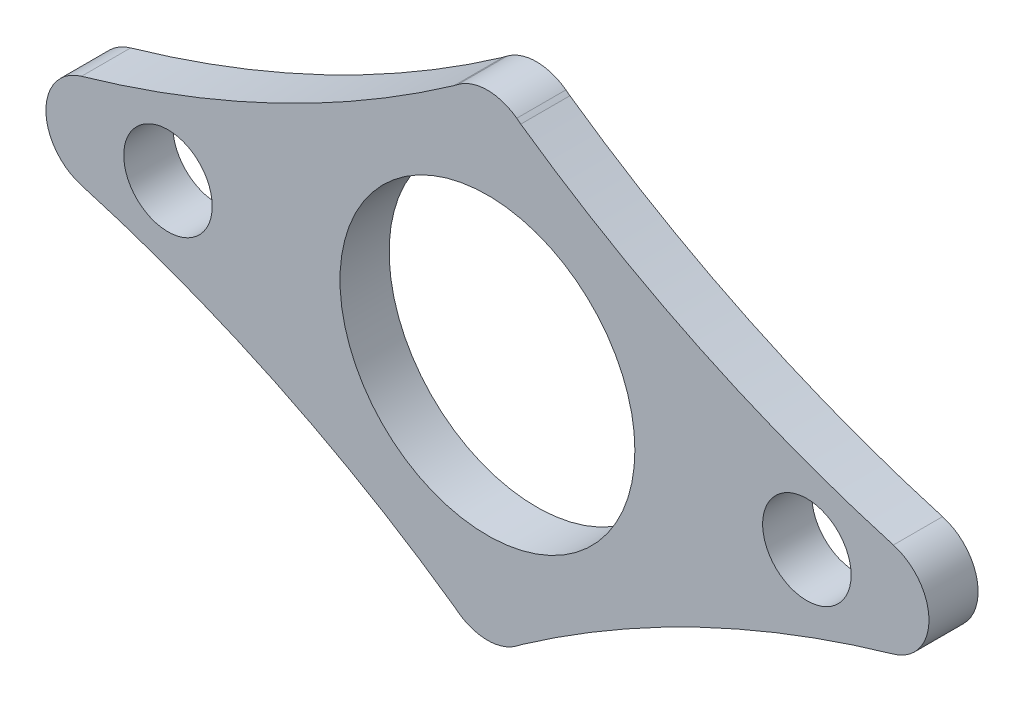
SolidWorks part; units mm, degrees
material "ABS"
ref_plane "Front Plane" through (0, 0, 0) normal (0, 0, 1) x (1, 0, 0)
ref_plane "Top Plane" through (0, 0, 0) normal (0, 1, 0) x (1, 0, 0)
ref_plane "Right Plane" through (0, 0, 0) normal (1, 0, 0) x (0, 0, -1)
sketch "Sketch1" plane through (0, 0, 0) normal (0, 0, 1) x (1, 0, 0)
  line L0 (-120, 0) -> (124.7467, 0) construction
  line L1 (0, 50) -> (0, -63.7109) construction
  line L2 (-65, 27.792) -> (-65, -23.9794) construction
  line L3 (65, 27.792) -> (65, -23.9794) construction
  circle A0 centre (0, 0) radius 30
  circle A1 centre (-65, 0) radius 9
  circle A2 centre (65, 0) radius 9
  arc A3 (-6.7849, 45.8702) -> (-94.7214, 6.4477) centre (-152.7826, 253.7474) cw
  arc A5 (-6.7849, 45.8702) -> (0, 50) centre (13.0163, 20.9769) cw
  arc A6 (6.7849, 45.8702) -> (0, 50) centre (-13.0163, 20.9769) ccw
  arc A7 (6.7849, 45.8702) -> (94.7214, 6.4477) centre (152.7826, 253.7474) ccw
  arc A10 (6.7849, -45.8702) -> (94.7214, -6.4477) centre (152.7826, -253.7474) cw
  arc A11 (6.7849, -45.8702) -> (0, -50) centre (-13.0163, -20.9769) cw
  arc A12 (-6.7849, -45.8702) -> (0, -50) centre (13.0163, -20.9769) ccw
  arc A14 (-6.7849, -45.8702) -> (-94.7214, -6.4477) centre (-152.7826, -253.7474) ccw
  arc A15 (-120, 0) -> (-94.7214, 6.4477) centre (-260.6871, 604.3504) ccw
  arc A16 (120, 0) -> (94.7214, 6.4477) centre (260.6871, 604.3504) cw
  arc A17 (120, 0) -> (94.7214, -6.4477) centre (260.6871, -604.3504) ccw
  arc A18 (-120, 0) -> (-94.7214, -6.4477) centre (-260.6871, -604.3504) cw
  dimension "D1" = 60
  dimension "D2" = 18
  dimension "D3" = 65
  dimension "D4" = 65
  dimension "D5" = 240
  dimension "D6" = 100
extrude "Boss-Extrude6" add sketch "Sketch1" along normal blind 10
fillet "Fillet3" radius 10 4 edges at (0, -50, 5) (120, 0, 5) (-120, 0, 5) (0, 50, 5)
